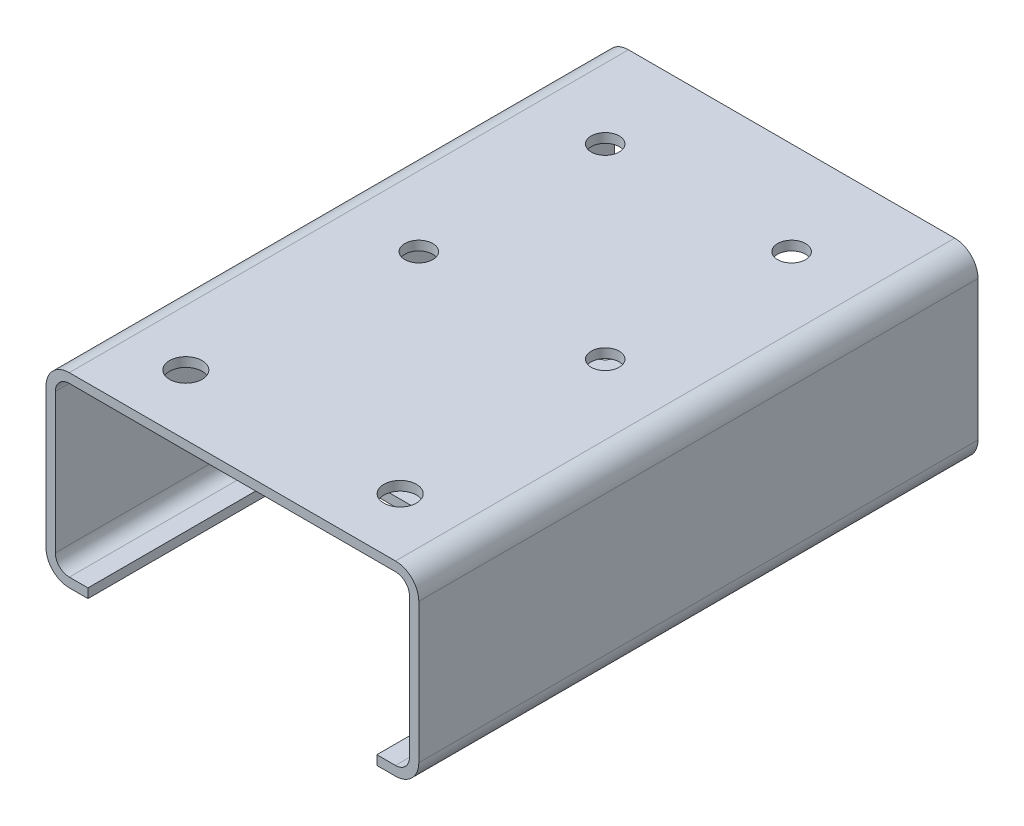
SolidWorks part; units mm, degrees
material "1.0038 (S235JRG2)"
ref_plane "Ebene vorne" through (0, 0, 0) normal (0, 0, 1) x (1, 0, 0)
ref_plane "Ebene oben" through (0, 0, 0) normal (0, 1, 0) x (1, 0, 0)
ref_plane "Ebene rechts" through (0, 0, 0) normal (1, 0, 0) x (0, 0, -1)
sketch "Skizze1" plane through (0, 0, 0) normal (0, 0, 1) x (1, 0, 0)
  line L0 (0, 35) -> (0, 5)
  line L1 (5, 0) -> (75, 0)
  line L2 (80, 5) -> (80, 35)
  line L5 (75, 40) -> (5, 40)
  line L6 (78, 5) -> (78, 35)
  line L7 (75, 38) -> (5, 38)
  line L8 (2, 35) -> (2, 5)
  line L9 (5, 2) -> (75, 2)
  arc A5 (80, 35) -> (75, 40) centre (75, 35) ccw
  arc A6 (75, 0) -> (80, 5) centre (75, 5) ccw
  arc A7 (0, 5) -> (5, 0) centre (5, 5) ccw
  arc A8 (5, 40) -> (0, 35) centre (5, 35) ccw
  arc A9 (78, 35) -> (75, 38) centre (75, 35) ccw
  arc A10 (5, 38) -> (2, 35) centre (5, 35) ccw
  arc A11 (2, 5) -> (5, 2) centre (5, 5) ccw
  arc A12 (75, 2) -> (78, 5) centre (75, 5) ccw
  point P13 (0, 0)
  dimension "D1" = 5
  dimension "D2" = 2
  dimension "D5" = 40
  dimension "D6" = 80
extrude "Aufsatz-Linear austragen1" add sketch "Skizze1" along normal blind 120
sketch "Skizze2" plane through (0, 0, 0) normal (0, -1, 0) x (1, 0, 0)
  line L0 (40, 0) -> (40, 93.0292) construction
  line L1 (5, 0) -> (75, 0) construction
  line L2 (5, 120) -> (75, 120) construction
  line L3 (9, 120) -> (71, 120)
  line L4 (9, 120) -> (9, 75)
  line L5 (14, 70) -> (66, 70)
  line L6 (71, 120) -> (71, 75)
  arc A0 (9, 75) -> (14, 70) centre (14, 75) ccw
  arc A1 (66, 70) -> (71, 75) centre (66, 75) ccw
  point P14 (71, 70)
  dimension "D3" = 5
  dimension "D1" = 62
  dimension "D2" = 50
extrude "Schnitt-Linear austragen1" cut sketch "Skizze2" against normal blind 10
sketch "Skizze3" plane through (0, 40, 0) normal (0, 1, 0) x (1, 0, 0)
  line L0 (40, 0) -> (40, -70.4701) construction
  line L1 (75, 0) -> (5, 0) construction
  line L2 (40, -40) -> (67.1501, -40) construction
  line L3 (75, -120) -> (5, -120) construction
  circle A0 centre (60, -20) radius 3
  circle A1 centre (20, -20) radius 3
  circle A2 centre (60, -60) radius 3
  circle A3 centre (20, -60) radius 3
  circle A4 centre (63, -107) radius 3.5
  circle A5 centre (17, -107) radius 3.5
  dimension "D1" = 40
  dimension "D2" = 40
  dimension "D4" = 6
  dimension "D5" = 46
  dimension "D6" = 47
  dimension "D7" = 7
  dimension "D8" = 13
  dimension "D3" = 40
extrude "Schnitt-Linear austragen2" cut sketch "Skizze3" against normal blind 60
